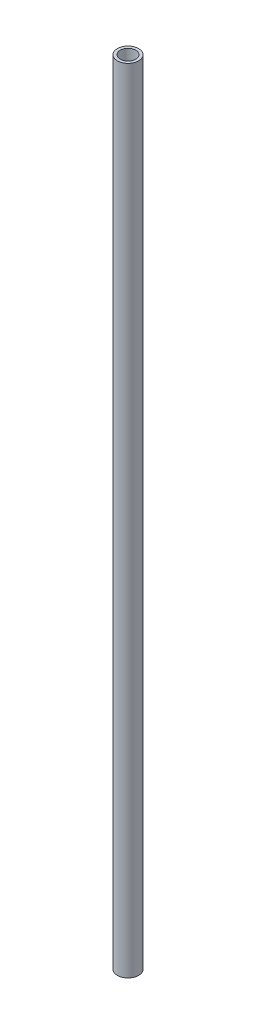
SolidWorks part; units mm, degrees
ref_plane "Front Plane" through (0, 0, 0) normal (0, 0, 1) x (1, 0, 0)
ref_plane "Top Plane" through (0, 0, 0) normal (0, 1, 0) x (1, 0, 0)
ref_plane "Right Plane" through (0, 0, 0) normal (1, 0, 0) x (0, 0, -1)
sketch "Sketch1" plane through (0, 0, 0) normal (0, 1, 0) x (1, 0, 0)
  circle A0 centre (0, 0) radius 9.525
  circle A1 centre (0, 0) radius 13
  dimension "D1" = 26
  dimension "D2" = 19.05
extrude "Boss-Extrude1" add sketch "Sketch1" along normal blind 967.74
